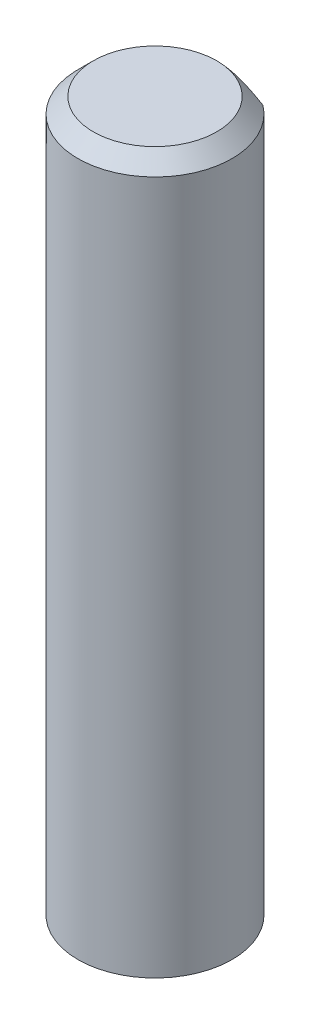
SolidWorks part; units mm, degrees
ref_plane "Front Plane" through (0, 0, 0) normal (0, 0, 1) x (1, 0, 0)
ref_plane "Top Plane" through (0, 0, 0) normal (0, 1, 0) x (1, 0, 0)
ref_plane "Right Plane" through (0, 0, 0) normal (1, 0, 0) x (0, 0, -1)
sketch "Sketch1" plane through (0, 0, 0) normal (0, 1, 0) x (1, 0, 0)
  circle A0 centre (0, 0) radius 2.5
  dimension "D1" = 5
extrude "Boss-Extrude1" add sketch "Sketch1" along normal blind 23
chamfer "Chamfer1" distance 0.5 angle 45 1 edges at (0, 23, 2.5)
sketch "Sketch2" plane through (0, 0, 0) normal (1, 0, 0) x (0, 0, -1)
  line L0 (0, 0) -> (0, 23) construction
  line L1 (2.5, 23) -> (-2.5, 23) construction
  line L2 (-2.5, 22.5) -> (-2.5, 0) construction
  line L3 (2, 23) -> (2.5, 23)
  line L4 (2, 23) -> (2, 5)
  line L5 (2, 5) -> (2.5, 5)
  line L6 (2.5, 23) -> (2.5, 5)
  dimension "D1" = 4.5
  dimension "D2" = 0.5
  dimension "D3" = 18
extrude "Cut-Extrude1" cut sketch "Sketch2" along normal through all both and the other way through all
